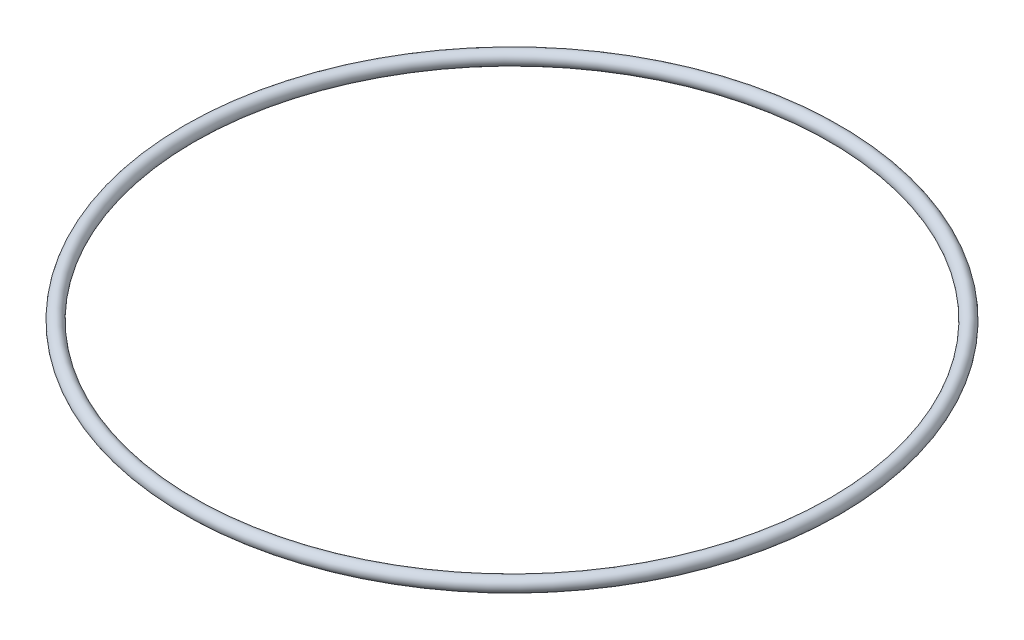
SolidWorks part; units mm, degrees
material "EPDM 60 Durometer"
ref_plane "Front Plane" through (0, 0, 0) normal (0, 0, 1) x (1, 0, 0)
ref_plane "Top Plane" through (0, 0, 0) normal (0, 1, 0) x (1, 0, 0)
ref_plane "Right Plane" through (0, 0, 0) normal (1, 0, 0) x (0, 0, -1)
sketch "Sketch3" plane through (0, 0, 0) normal (0, 1, 0) x (1, 0, 0)
  circle A0 centre (0, 0) radius 71.35
  dimension "D1" = 142.7
sketch "Sketch5" plane through (0, 0, 0) normal (0, 0, 1) x (1, 0, 0)
  line L0 (71.35, 0) -> (-71.35, 0) construction
  circle A0 centre (71.35, 0) radius 1.5
  point P4 (0, 0)
  dimension "D1" = 3
  dimension "D2" = 71.35
sweep "Sweep1" add profiles "Sketch5" path "Sketch3"
equation "\"Diameter Top\"= 142.7mm"
equation "\"Thickness O'ring\" = 3.00mm"
equation "\"D1@Sketch5\"=\"Thickness O'ring\"''"
equation "\"D1@Sketch3\"=\"Diameter Top\""
